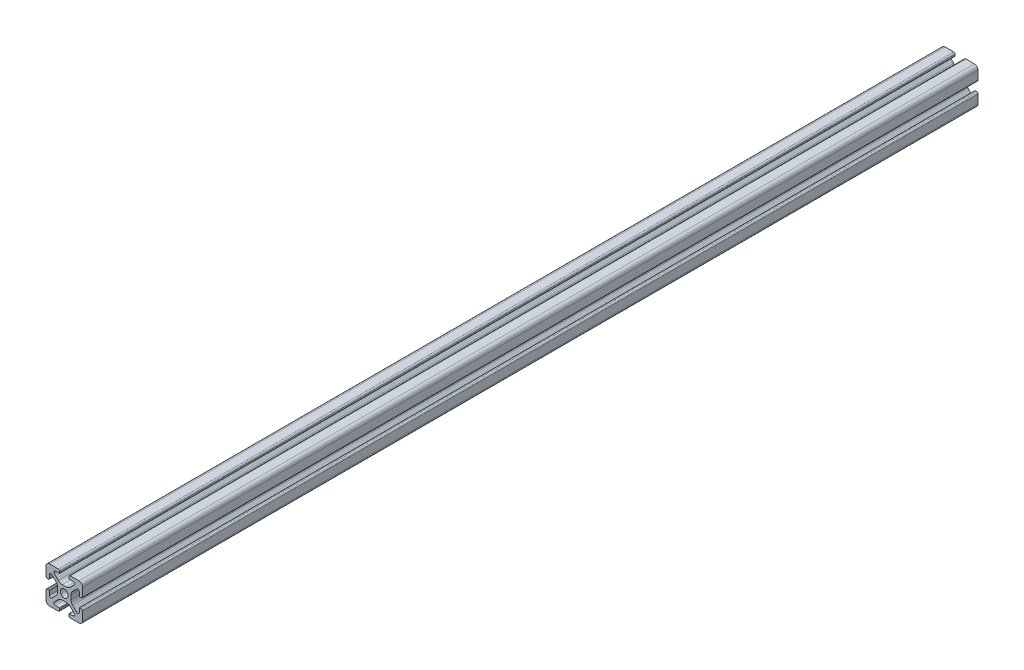
SolidWorks part; units mm, degrees
material "3.0205 (EN-AW 1200)"
ref_plane "Plan de face" through (0, 0, 0) normal (0, 0, 1) x (1, 0, 0)
ref_plane "Plan de dessus" through (0, 0, 0) normal (0, 1, 0) x (1, 0, 0)
ref_plane "Plan de droite" through (0, 0, 0) normal (1, 0, 0) x (0, 0, -1)
ref_plane "Plan1" through (0, 0, 0) normal (0, 0, -1) x (-1, 0, 0)
sketch "Esquisse1" plane through (0, 0, 0) normal (0, 0, -1) x (-1, 0, 0)
  line L0 (-12.5, 0.8) -> (-12.5, 1.5)
  line L1 (-12.8, 1.8) -> (-14.9176, 1.8)
  line L2 (-15.5062, 3.221) -> (-13.2559, 5.4713)
  line L3 (-11.1346, 6.35) -> (-8.8654, 6.35)
  line L4 (-6.7441, 5.4713) -> (-4.4938, 3.221)
  line L5 (-5.0824, 1.8) -> (-7.2, 1.8)
  line L6 (-7.5, 1.5) -> (-7.5, 0.8)
  line L7 (-6.7, 0) -> (-2, 0)
  line L8 (0, 2) -> (0, 6.7)
  line L9 (-0.8, 7.5) -> (-1.5, 7.5)
  line L10 (-1.8, 7.2) -> (-1.8, 5.0824)
  line L11 (-3.221, 4.4938) -> (-5.4713, 6.7441)
  line L12 (-6.35, 8.8654) -> (-6.35, 11.1346)
  line L13 (-5.4713, 13.2559) -> (-3.221, 15.5062)
  line L14 (-1.8, 14.9176) -> (-1.8, 12.8)
  line L15 (-1.5, 12.5) -> (-0.8, 12.5)
  line L16 (0, 13.3) -> (0, 18)
  line L17 (-2, 20) -> (-6.7, 20)
  line L18 (-7.5, 19.2) -> (-7.5, 18.5)
  line L19 (-7.2, 18.2) -> (-5.0824, 18.2)
  line L20 (-4.4938, 16.779) -> (-6.7441, 14.5287)
  line L21 (-8.8654, 13.65) -> (-11.1346, 13.65)
  line L22 (-13.2559, 14.5287) -> (-15.5062, 16.779)
  line L23 (-14.9176, 18.2) -> (-12.8, 18.2)
  line L24 (-12.5, 18.5) -> (-12.5, 19.2)
  line L25 (-13.3, 20) -> (-18, 20)
  line L26 (-20, 18) -> (-20, 13.3)
  line L27 (-19.2, 12.5) -> (-18.5, 12.5)
  line L28 (-18.2, 12.8) -> (-18.2, 14.9176)
  line L29 (-16.779, 15.5062) -> (-14.5287, 13.2559)
  line L30 (-13.65, 11.1346) -> (-13.65, 8.8654)
  line L31 (-14.5287, 6.7441) -> (-16.779, 4.4938)
  line L32 (-18.2, 5.0824) -> (-18.2, 7.2)
  line L33 (-18.5, 7.5) -> (-19.2, 7.5)
  line L34 (-20, 6.7) -> (-20, 2)
  line L35 (-18, 0) -> (-13.3, 0)
  arc A0 (-12.5, 1.5) -> (-12.8, 1.8) centre (-12.8, 1.5) ccw
  arc A1 (-14.9176, 1.8) -> (-15.5062, 3.221) centre (-14.9176, 2.6324) cw
  arc A2 (-13.2559, 5.4713) -> (-11.1346, 6.35) centre (-11.1346, 3.35) cw
  arc A3 (-8.8654, 6.35) -> (-6.7441, 5.4713) centre (-8.8654, 3.35) cw
  arc A4 (-4.4938, 3.221) -> (-5.0824, 1.8) centre (-5.0824, 2.6324) cw
  arc A5 (-7.2, 1.8) -> (-7.5, 1.5) centre (-7.2, 1.5) ccw
  arc A6 (-7.5, 0.8) -> (-6.7, 0) centre (-6.7, 0.8) ccw
  arc A7 (-2, 0) -> (0, 2) centre (-2, 2) ccw
  arc A8 (0, 6.7) -> (-0.8, 7.5) centre (-0.8, 6.7) ccw
  arc A9 (-1.5, 7.5) -> (-1.8, 7.2) centre (-1.5, 7.2) ccw
  arc A10 (-1.8, 5.0824) -> (-3.221, 4.4938) centre (-2.6324, 5.0824) cw
  arc A11 (-5.4713, 6.7441) -> (-6.35, 8.8654) centre (-3.35, 8.8654) cw
  arc A12 (-6.35, 11.1346) -> (-5.4713, 13.2559) centre (-3.35, 11.1346) cw
  arc A13 (-3.221, 15.5062) -> (-1.8, 14.9176) centre (-2.6324, 14.9176) cw
  arc A14 (-1.8, 12.8) -> (-1.5, 12.5) centre (-1.5, 12.8) ccw
  arc A15 (-0.8, 12.5) -> (0, 13.3) centre (-0.8, 13.3) ccw
  arc A16 (0, 18) -> (-2, 20) centre (-2, 18) ccw
  arc A17 (-6.7, 20) -> (-7.5, 19.2) centre (-6.7, 19.2) ccw
  arc A18 (-7.5, 18.5) -> (-7.2, 18.2) centre (-7.2, 18.5) ccw
  arc A19 (-5.0824, 18.2) -> (-4.4938, 16.779) centre (-5.0824, 17.3676) cw
  arc A20 (-6.7441, 14.5287) -> (-8.8654, 13.65) centre (-8.8654, 16.65) cw
  arc A21 (-11.1346, 13.65) -> (-13.2559, 14.5287) centre (-11.1346, 16.65) cw
  arc A22 (-15.5062, 16.779) -> (-14.9176, 18.2) centre (-14.9176, 17.3676) cw
  arc A23 (-12.8, 18.2) -> (-12.5, 18.5) centre (-12.8, 18.5) ccw
  arc A24 (-12.5, 19.2) -> (-13.3, 20) centre (-13.3, 19.2) ccw
  arc A25 (-18, 20) -> (-20, 18) centre (-18, 18) ccw
  arc A26 (-20, 13.3) -> (-19.2, 12.5) centre (-19.2, 13.3) ccw
  arc A27 (-18.5, 12.5) -> (-18.2, 12.8) centre (-18.5, 12.8) ccw
  arc A28 (-18.2, 14.9176) -> (-16.779, 15.5062) centre (-17.3676, 14.9176) cw
  arc A29 (-14.5287, 13.2559) -> (-13.65, 11.1346) centre (-16.65, 11.1346) cw
  arc A30 (-13.65, 8.8654) -> (-14.5287, 6.7441) centre (-16.65, 8.8654) cw
  arc A31 (-16.779, 4.4938) -> (-18.2, 5.0824) centre (-17.3676, 5.0824) cw
  arc A32 (-18.2, 7.2) -> (-18.5, 7.5) centre (-18.5, 7.2) ccw
  arc A33 (-19.2, 7.5) -> (-20, 6.7) centre (-19.2, 6.7) ccw
  arc A34 (-20, 2) -> (-18, 0) centre (-18, 2) ccw
  arc A35 (-13.3, 0) -> (-12.5, 0.8) centre (-13.3, 0.8) ccw
  circle A36 centre (-10, 10) radius 2.15
extrude "Boss.-Extru.1" add sketch "Esquisse1" against normal blind 490
